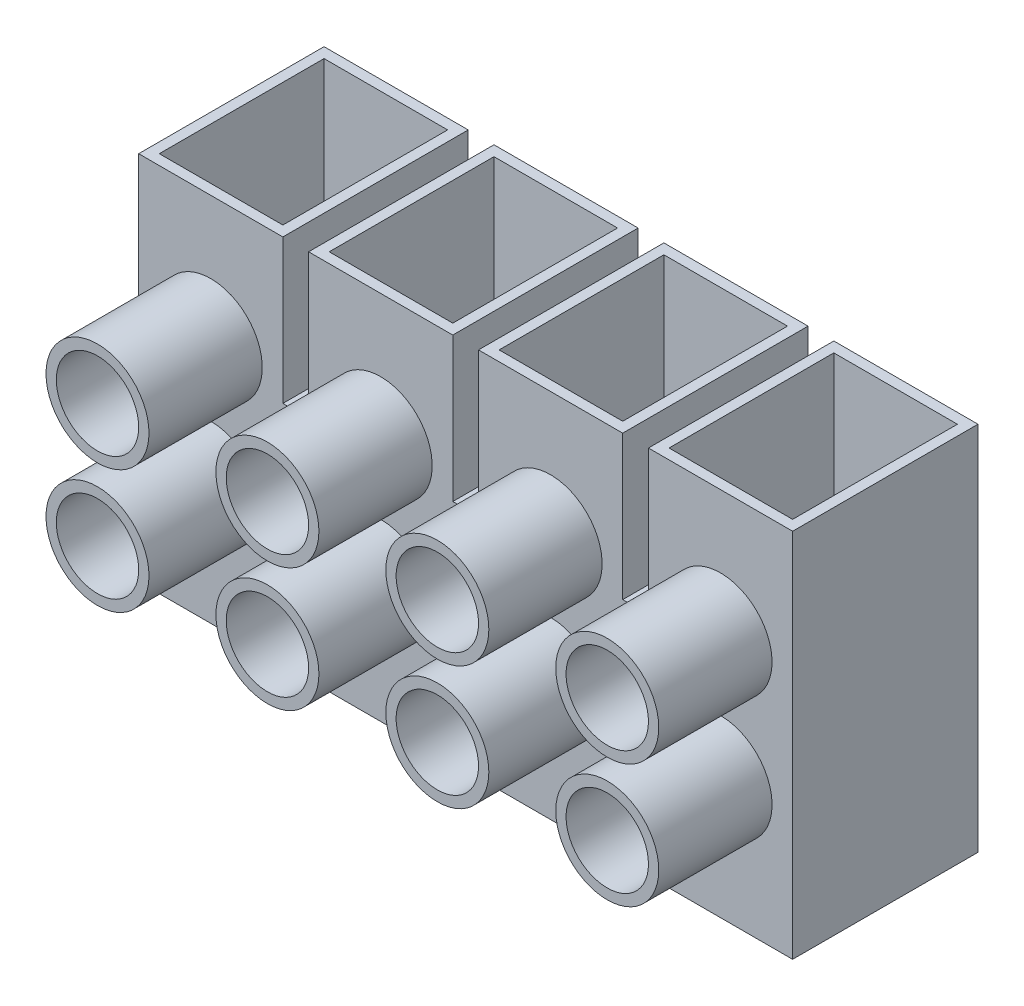
SolidWorks part; units mm, degrees
ref_plane "Alzado" through (0, 0, 0) normal (0, 0, 1) x (1, 0, 0)
ref_plane "Planta" through (0, 0, 0) normal (0, 1, 0) x (1, 0, 0)
ref_plane "Vista lateral" through (0, 0, 0) normal (1, 0, 0) x (0, 0, -1)
sketch "Croquis1" plane through (0, 0, 0) normal (0, 0, 1) x (1, 0, 0)
  line L0 (8.25, 0) -> (15.25, 0)
  line L1 (0, 0) -> (7, 0)
  line L2 (0, 0) -> (0, 18)
  line L3 (0, 18) -> (7, 18)
  line L4 (7, 0) -> (7, 18)
  line L5 (15.25, 0) -> (15.25, 18)
  line L6 (8.25, 18) -> (15.25, 18)
  line L7 (8.25, 0) -> (8.25, 18)
  line L8 (16.5, 0) -> (23.5, 0)
  line L9 (23.5, 0) -> (23.5, 18)
  line L10 (16.5, 18) -> (23.5, 18)
  line L11 (16.5, 0) -> (16.5, 18)
  line L12 (24.75, 0) -> (31.75, 0)
  line L13 (31.75, 0) -> (31.75, 18)
  line L14 (24.75, 18) -> (31.75, 18)
  line L15 (24.75, 0) -> (24.75, 18)
  line L24 (33, 0) -> (40, 0) [skipped]
  line L25 (40, 0) -> (40, 18) [skipped]
  line L26 (33, 18) -> (40, 18) [skipped]
  line L27 (33, 0) -> (33, 18) [skipped]
  line L28 (41.25, 0) -> (48.25, 0) [skipped]
  line L29 (48.25, 0) -> (48.25, 18) [skipped]
  line L30 (41.25, 18) -> (48.25, 18) [skipped]
  line L31 (41.25, 0) -> (41.25, 18) [skipped]
  dimension "D1" = 7
  dimension "D2" = 18
  dimension "D3" = 6
extrude "Saliente-Extruir1" add sketch "Croquis1" along normal blind 9
sketch "Croquis2" plane through (0, 0, 0) normal (0, 0, 1) x (1, 0, 0)
  line L0 (0, 9) -> (24.75, 9) construction
  line L1 (0, 18) -> (0, 0) construction
  line L3 (0, 7) -> (24.75, 7)
  line L4 (0, 11) -> (24.75, 11)
  line L5 (0, 7) -> (0, 11)
  line L6 (24.75, 7) -> (24.75, 11)
  line L7 (0, 9) -> (24.75, 9) construction
  line L8 (24.75, 18) -> (24.75, 0) construction
  dimension "D1" = 2
  dimension "D2" = 2
extrude "Saliente-Extruir2" add sketch "Croquis2" along normal blind 9
sketch "Croquis3" plane through (0, 0, 9) normal (0, 0, 1) x (1, 0, 0)
  line L0 (0, 9) -> (31.75, 9) construction
  line L1 (0, 18) -> (0, 0) construction
  line L3 (31.75, 0) -> (31.75, 18) construction
  circle A0 centre (3.5, 12) radius 2.5
  circle A1 centre (3.5, 12) radius 2
  circle A2 centre (11.75, 12) radius 2.5
  circle A3 centre (11.75, 12) radius 2
  circle A4 centre (20, 12) radius 2.5
  circle A5 centre (20, 12) radius 2
  circle A6 centre (28.25, 12) radius 2.5
  circle A7 centre (28.25, 12) radius 2
  circle A12 centre (11.75, 6) radius 2.5
  circle A13 centre (11.75, 6) radius 2
  circle A14 centre (20, 6) radius 2.5
  circle A15 centre (20, 6) radius 2
  circle A16 centre (28.25, 6) radius 2.5
  circle A17 centre (28.25, 6) radius 2
  circle A22 centre (3.5, 6) radius 2.5
  circle A23 centre (3.5, 6) radius 2
  circle A24 centre (36.5, 12) radius 2.5 [skipped]
  circle A25 centre (36.5, 12) radius 2 [skipped]
  circle A26 centre (44.75, 12) radius 2.5 [skipped]
  circle A27 centre (44.75, 12) radius 2 [skipped]
  circle A28 centre (36.5, 6) radius 2.5 [skipped]
  circle A29 centre (36.5, 6) radius 2 [skipped]
  circle A30 centre (44.75, 6) radius 2.5 [skipped]
  circle A31 centre (44.75, 6) radius 2 [skipped]
  dimension "D1" = 3
  dimension "D2" = 3
  dimension "D3" = 3.5
  dimension "D4" = 3.5
  dimension "D5" = 5
  dimension "D6" = 4
  dimension "D7" = 6
  dimension "D8" = 2
extrude "Saliente-Extruir3" add sketch "Croquis3" along normal blind 5.5
sketch "Croquis4" plane through (0, 0, 9) normal (0, 0, 1) x (1, 0, 0)
  line L0 (0, 9) -> (31.75, 9) construction
  line L1 (0, 18) -> (0, 0) construction
  line L3 (31.75, 0) -> (31.75, 18) construction
  circle A0 centre (7.625, 9) radius 1
  circle A1 centre (15.875, 9) radius 1
  circle A2 centre (24.125, 9) radius 1
  circle A5 centre (32.375, 9) radius 1 [skipped]
  circle A6 centre (40.625, 9) radius 1 [skipped]
  dimension "D1" = 2
  dimension "D2" = 7.625
  dimension "D3" = 5
extrude "Cortar-Extruir1" cut sketch "Croquis4" against normal through all
sketch "Croquis5" plane through (0, 0, 0) normal (0, -1, 0) x (1, 0, 0)
  line L0 (0.5, 0.5) -> (6.5, 0.5)
  line L1 (0, 0) -> (7, 0) construction
  line L2 (0, 0) -> (0, 9) construction
  line L3 (0, 9) -> (7, 9) construction
  line L4 (7, 0) -> (7, 9) construction
  line L5 (6.5, 0.5) -> (6.5, 8.5)
  line L6 (0.5, 8.5) -> (6.5, 8.5)
  line L7 (0.5, 0.5) -> (0.5, 8.5)
  line L8 (8.75, 0.5) -> (14.75, 0.5)
  line L9 (8.75, 0.5) -> (8.75, 8.5)
  line L10 (8.75, 8.5) -> (14.75, 8.5)
  line L11 (14.75, 0.5) -> (14.75, 8.5)
  line L12 (17, 0.5) -> (23, 0.5)
  line L13 (17, 0.5) -> (17, 8.5)
  line L14 (17, 8.5) -> (23, 8.5)
  line L15 (23, 0.5) -> (23, 8.5)
  line L16 (25.25, 0.5) -> (31.25, 0.5)
  line L17 (25.25, 0.5) -> (25.25, 8.5)
  line L18 (25.25, 8.5) -> (31.25, 8.5)
  line L19 (31.25, 0.5) -> (31.25, 8.5)
  line L28 (33.5, 0.5) -> (39.5, 0.5) [skipped]
  line L29 (33.5, 0.5) -> (33.5, 8.5) [skipped]
  line L30 (33.5, 8.5) -> (39.5, 8.5) [skipped]
  line L31 (39.5, 0.5) -> (39.5, 8.5) [skipped]
  line L32 (41.75, 0.5) -> (47.75, 0.5) [skipped]
  line L33 (41.75, 0.5) -> (41.75, 8.5) [skipped]
  line L34 (41.75, 8.5) -> (47.75, 8.5) [skipped]
  line L35 (47.75, 0.5) -> (47.75, 8.5) [skipped]
  dimension "D1" = 0.5
  dimension "D2" = 6
extrude "Cortar-Extruir2" cut sketch "Croquis5" against normal through all
equation "\"D2@Croquis4\"=7+1.25/2"
